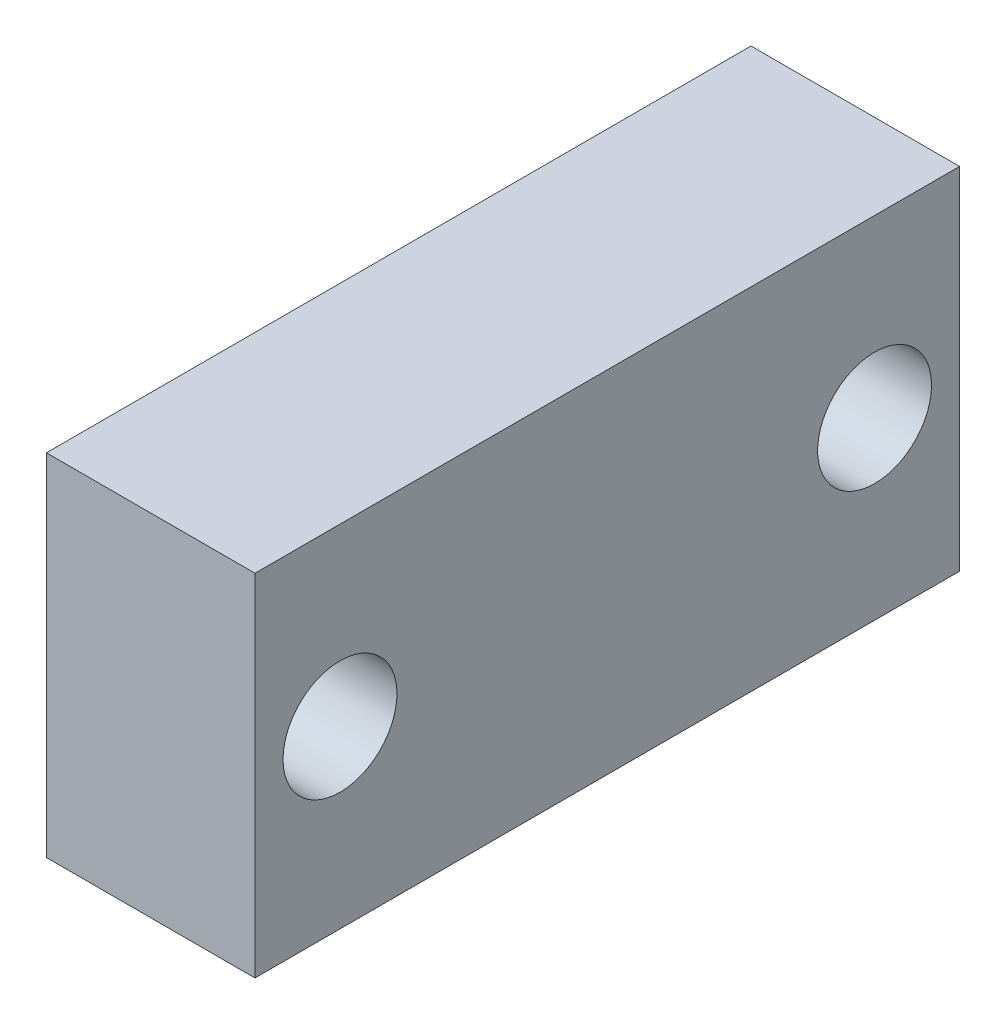
SolidWorks part; units mm, degrees
ref_plane "Front Plane" through (0, 0, 0) normal (0, 0, 1) x (1, 0, 0)
ref_plane "Top Plane" through (0, 0, 0) normal (0, 1, 0) x (1, 0, 0)
ref_plane "Right Plane" through (0, 0, 0) normal (1, 0, 0) x (0, 0, -1)
sketch "Sketch1" plane through (0, 0, 0) normal (1, 0, 0) x (0, 0, -1)
  line L1 (-20.1, 10) -> (20.1, 10)
  line L2 (-20.1, 10) -> (-20.1, -10)
  line L3 (-20.1, -10) -> (20.1, -10)
  line L4 (20.1, 10) -> (20.1, -10)
  line L5 (-20.1, 10) -> (20.1, -10) construction
  line L6 (-20.1, -10) -> (20.1, 10) construction
  point P0 (0, 0)
  dimension "D1" = 40.2
  dimension "D2" = 20
extrude "Boss-Extrude1" add sketch "Sketch1" along normal blind 11.9
sketch "Sketch2" plane through (0, -10, 0) normal (0, -1, 0) x (1, 0, 0)
  line L0 (0, 0) -> (3.37, 0) construction
  line L1 (0, 20.1) -> (0, -20.1) construction
  line L2 (6.74, 0) -> (6.04, 0) construction
  line L3 (6.74, 9.4) -> (0, 9.4) construction
  line L4 (6.74, 9.4) -> (6.74, -9.4) construction
  line L5 (6.74, -9.4) -> (0, -9.4) construction
  line L6 (0, 9.4) -> (0, -9.4) construction
  line L7 (6.74, 9.4) -> (0, -9.4) construction
  line L8 (6.74, -9.4) -> (0, 9.4) construction
  line L9 (6.04, 0) -> (1.74, 0) construction
  line L10 (3.89, 0) -> (3.89, -9.4) construction
  line L11 (3.37, -9.4) -> (3.37, -7.1) construction
  line L12 (3.37, -7.1) -> (3.37, -2.7) construction
  line L13 (3.37, -4.9) -> (3.89, -4.9) construction
  circle A0 centre (3.89, -4.9) radius 2.35
  circle A1 centre (3.89, 4.9) radius 2.35
  dimension "D7" = 4.7
  dimension "D1" = 3.37
  dimension "D2" = 18.8
  dimension "D3" = 0.7
  dimension "D4" = 4.3
  dimension "D5" = 2.3
  dimension "D6" = 4.4
extrude "Cut-Extrude1" cut sketch "Sketch2" against normal blind 10
sketch "Sketch3" plane through (11.9, 0, 0) normal (1, 0, 0) x (0, 0, -1)
  line L0 (-20.1, -10) -> (20.1, -10) construction
  line L1 (20.1, 10) -> (10.4, 10)
  line L2 (20.1, 10) -> (20.1, -10)
  line L3 (20.1, -10) -> (10.4, -10)
  line L4 (10.4, 10) -> (10.4, -10)
  line L5 (20.1, 10) -> (10.4, -10) construction
  line L6 (20.1, -10) -> (10.4, 10) construction
  line L7 (0, 0) -> (0, -7.0234) construction
  circle A0 centre (15.25, 0) radius 2
  circle A1 centre (-15.25, 0) radius 2
  point P4 (15.25, 0)
  dimension "D2" = 4
  dimension "D1" = 9.7
extrude "Cut-Extrude3" cut sketch "Sketch3" against normal through all contours A0 | A1
sketch "Sketch5" plane through (11.9, 0, 0) normal (1, 0, 0) x (0, 0, -1)
  line L0 (-20.1, -10) -> (20.1, -10) construction
  line L1 (20.1, 10) -> (10.4, 10)
  line L2 (20.1, 10) -> (20.1, -10)
  line L3 (20.1, -10) -> (10.4, -10)
  line L4 (10.4, 10) -> (10.4, -10)
  line L5 (20.1, 10) -> (10.4, -10) construction
  line L6 (20.1, -10) -> (10.4, 10) construction
  line L7 (0, 0) -> (0, -6.2882) construction
  circle A0 centre (15.25, 0) radius 3.25
  circle A1 centre (-15.25, 0) radius 3.25
  point P4 (15.25, 0)
  dimension "D2" = 6.5
  dimension "D1" = 9.7
extrude "Cut-Extrude4" cut sketch "Sketch5" against normal blind 9 contours A0 | A1
chamfer "Chamfer1" distance 1 angle 45 2 edges at (3.89, -10, 7.25) (3.89, -10, -7.25)
